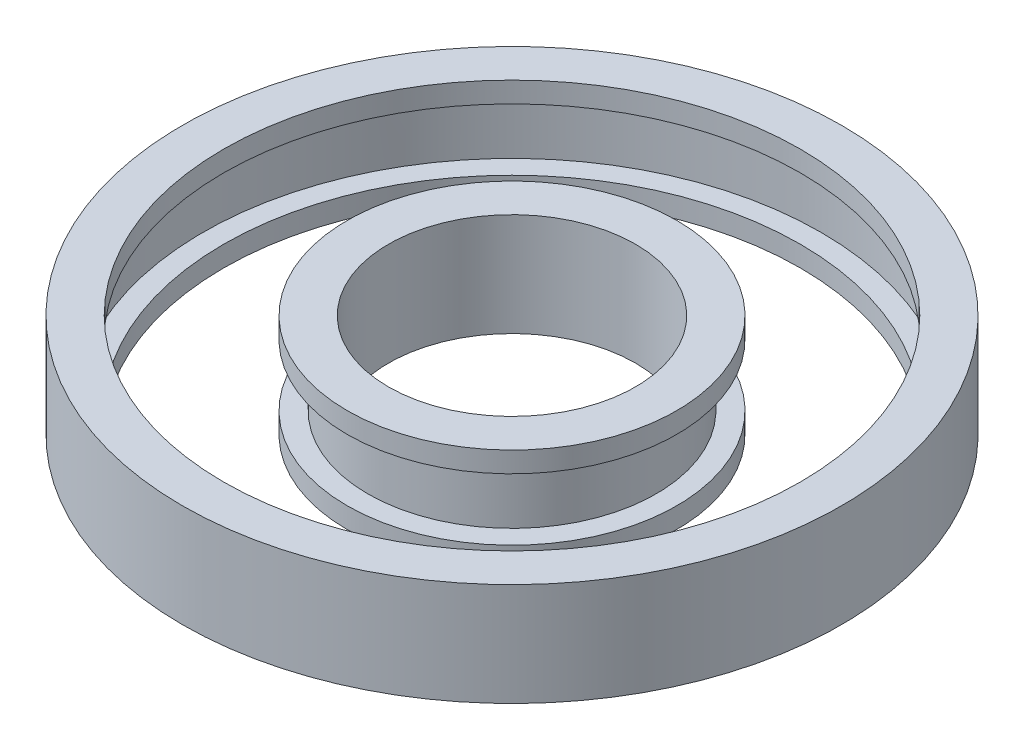
SolidWorks part; units mm, degrees
ref_plane "Front Plane" through (0, 0, 0) normal (0, 0, 1) x (1, 0, 0)
ref_plane "Top Plane" through (0, 0, 0) normal (0, 1, 0) x (1, 0, 0)
ref_plane "Right Plane" through (0, 0, 0) normal (1, 0, 0) x (0, 0, -1)
sketch "Sketch21" plane through (0, 0, 0) normal (0, 1, 0) x (1, 0, 0)
  circle A0 centre (-29.8525, -11.5251) radius 32
  circle A1 centre (-29.8525, -11.5251) radius 30
extrude "Boss-Extrude1" add sketch "Sketch21" along normal blind 10
sketch "Sketch22" plane through (0, 0, 0) normal (0, -1, 0) x (1, 0, 0)
  circle A0 centre (-29.8525, 11.5251) radius 30 construction
  circle A1 centre (-29.8525, 11.5251) radius 30
  circle A2 centre (-29.8525, 11.5251) radius 12
  circle A3 centre (-29.8525, 11.5251) radius 14
extrude "Boss-Extrude2" add sketch "Sketch22" against normal blind 10 separate body contours A3 A2
sketch "Sketch23" plane through (0, 0, 0) normal (0, -1, 0) x (1, 0, 0)
  circle A1 centre (-29.8525, 11.5251) radius 28
  circle A2 centre (-29.8525, 11.5251) radius 30 construction
  circle A3 centre (-29.8525, 11.5251) radius 30
extrude "Boss-Extrude3" add sketch "Sketch23" against normal blind 2
sketch "Sketch24" plane through (0, 0, 0) normal (0, -1, 0) x (1, 0, 0)
  circle A1 centre (-29.8525, 11.5251) radius 28 construction
  circle A2 centre (-29.8525, 11.5251) radius 28
  circle A3 centre (-29.8525, 11.5251) radius 16
  circle A4 centre (-29.8525, 11.5251) radius 14 construction
  circle A5 centre (-29.8525, 11.5251) radius 14
  circle M2 centre (-29.8525, 11.5251) radius 14
extrude "Boss-Extrude4" add sketch "Sketch24" against normal blind 2 contours A3 M2
sketch "Sketch25" plane through (0, 10, 0) normal (0, 1, 0) x (1, 0, 0)
  circle A0 centre (-29.8525, -11.5251) radius 28
  circle A1 centre (-29.8525, -11.5251) radius 30 construction
  circle A2 centre (-29.8525, -11.5251) radius 30
extrude "Boss-Extrude5" add sketch "Sketch25" against normal blind 2
sketch "Sketch26" plane through (0, 10, 0) normal (0, 1, 0) x (1, 0, 0)
  circle A0 centre (-29.8525, -11.5251) radius 16
  circle A1 centre (-29.8525, -11.5251) radius 14 construction
  circle A2 centre (-29.8525, -11.5251) radius 14
extrude "Boss-Extrude6" add sketch "Sketch26" against normal blind 2
